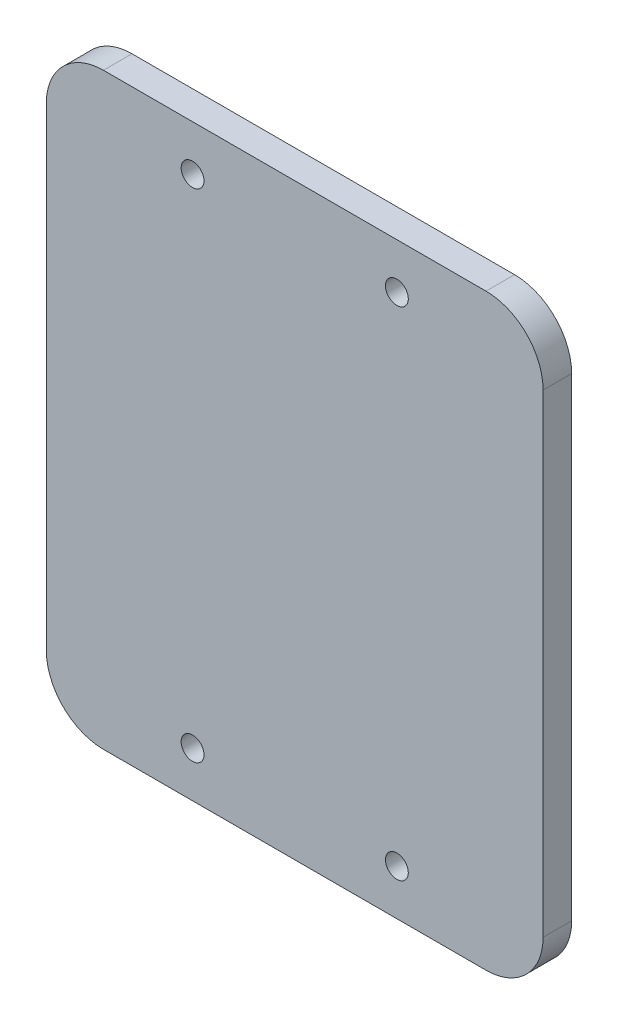
SolidWorks part; units mm, degrees
ref_plane "Alzado" through (0, 0, 0) normal (0, 0, 1) x (1, 0, 0)
ref_plane "Planta" through (0, 0, 0) normal (0, 1, 0) x (1, 0, 0)
ref_plane "Vista lateral" through (0, 0, 0) normal (1, 0, 0) x (0, 0, -1)
sketch "Croquis1" plane through (0, 0, 0) normal (0, 0, 1) x (1, 0, 0)
  line L0 (-30.1092, -31.3172) -> (56.8908, -31.3172) construction
  line L1 (-30.1092, 20.1828) -> (56.8908, 20.1828)
  line L2 (-30.1092, 20.1828) -> (-30.1092, -82.8172)
  line L3 (-30.1092, -82.8172) -> (56.8908, -82.8172)
  line L4 (56.8908, 20.1828) -> (56.8908, -82.8172)
  line L6 (13.3908, 20.1828) -> (13.3908, -82.8172) construction
  circle A0 centre (-4.4992, 12.2028) radius 2
  circle A1 centre (31.2808, 12.2028) radius 2
  circle A2 centre (31.2808, -74.8372) radius 2
  circle A3 centre (-4.4992, -74.8372) radius 2
  dimension "D3" = 4
  dimension "D4" = 43.52
  dimension "D5" = 17.89
  dimension "D1" = 87
  dimension "D2" = 103
extrude "Saliente-Extruir1" add sketch "Croquis1" along normal blind 5
fillet "Redondeo1" radius 10 4 edges at (-30.1092, -82.8172, 2.5) (56.8908, -82.8172, 2.5) (56.8908, 20.1828, 2.5) (-30.1092, 20.1828, 2.5)
